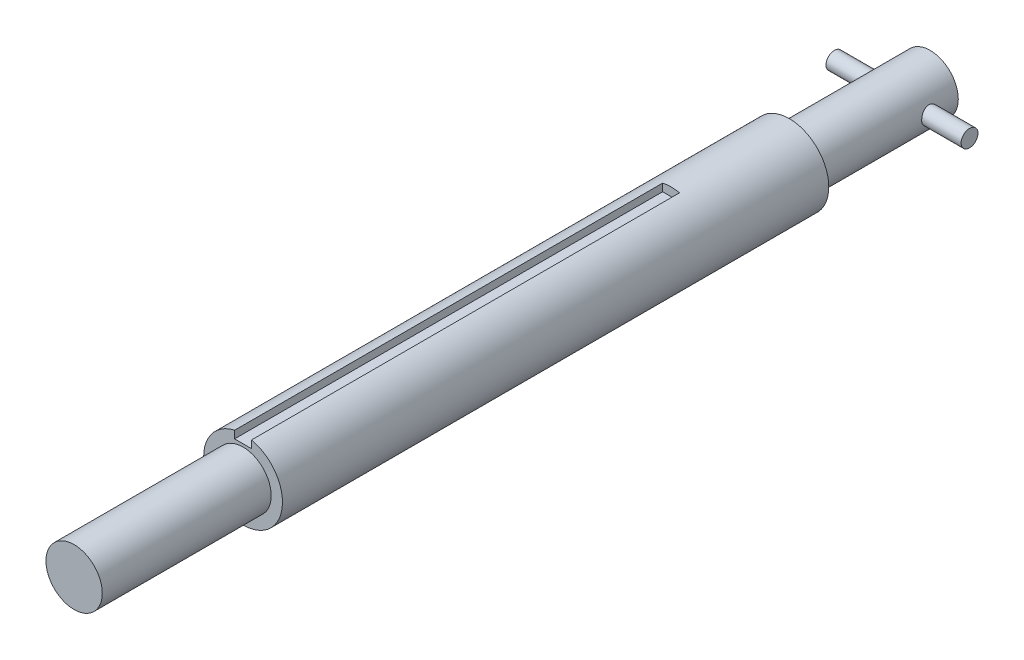
SolidWorks part; units mm, degrees
ref_plane "Front Plane" through (0, 0, 0) normal (0, 0, 1) x (1, 0, 0)
ref_plane "Top Plane" through (0, 0, 0) normal (0, 1, 0) x (1, 0, 0)
ref_plane "Right Plane" through (0, 0, 0) normal (1, 0, 0) x (0, 0, -1)
sketch "Sketch1" plane through (0, 0, 0) normal (0, 0, 1) x (1, 0, 0)
  circle A0 centre (0, 0) radius 5
  dimension "D1" = 10
extrude "Boss-Extrude1" add sketch "Sketch1" along normal blind 25
sketch "Sketch2" plane through (0, 0, 25) normal (0, 0, 1) x (1, 0, 0)
  circle A0 centre (0, 0) radius 7
  dimension "D1" = 14
extrude "Boss-Extrude2" add sketch "Sketch2" along normal blind 97
sketch "Sketch3" plane through (0, 0, 122) normal (0, 0, 1) x (1, 0, 0)
  circle A0 centre (0, 0) radius 5
  dimension "D1" = 10
extrude "Boss-Extrude3" add sketch "Sketch3" along normal blind 30
sketch "Sketch4" plane through (0, 0, 0) normal (0, 1, 0) x (1, 0, 0)
  line L0 (-5, -122) -> (5, -122) construction
  line L1 (-1.5, -46) -> (1.5, -46)
  line L2 (-1.5, -46) -> (-1.5, -122)
  line L3 (-1.5, -122) -> (1.5, -122)
  line L4 (1.5, -46) -> (1.5, -122)
  point P6 (0, -122)
  dimension "D1" = 3
  dimension "D2" = 76
extrude "Cut-Extrude1" cut sketch "Sketch4" against normal blind 1.5 from offset 7
sketch "Sketch5" plane through (0, 0, 0) normal (1, 0, 0) x (0, 0, -1)
  line L0 (-25, -7) -> (-25, 7) construction
  circle A0 centre (-5, 0) radius 1.5
  dimension "D1" = 3
  dimension "D2" = 20
extrude "Cut-Extrude2" cut sketch "Sketch5" against normal through all both and the other way through all
sketch "Sketch6" plane through (0, 0, 0) normal (1, 0, 0) x (0, 0, -1)
  circle A0 centre (-5, 0) radius 1.5 construction
  circle A1 centre (-5, 0) radius 1.5
extrude "Boss-Extrude4" add sketch "Sketch6" along normal blind 12 and the other way blind 12 separate body
